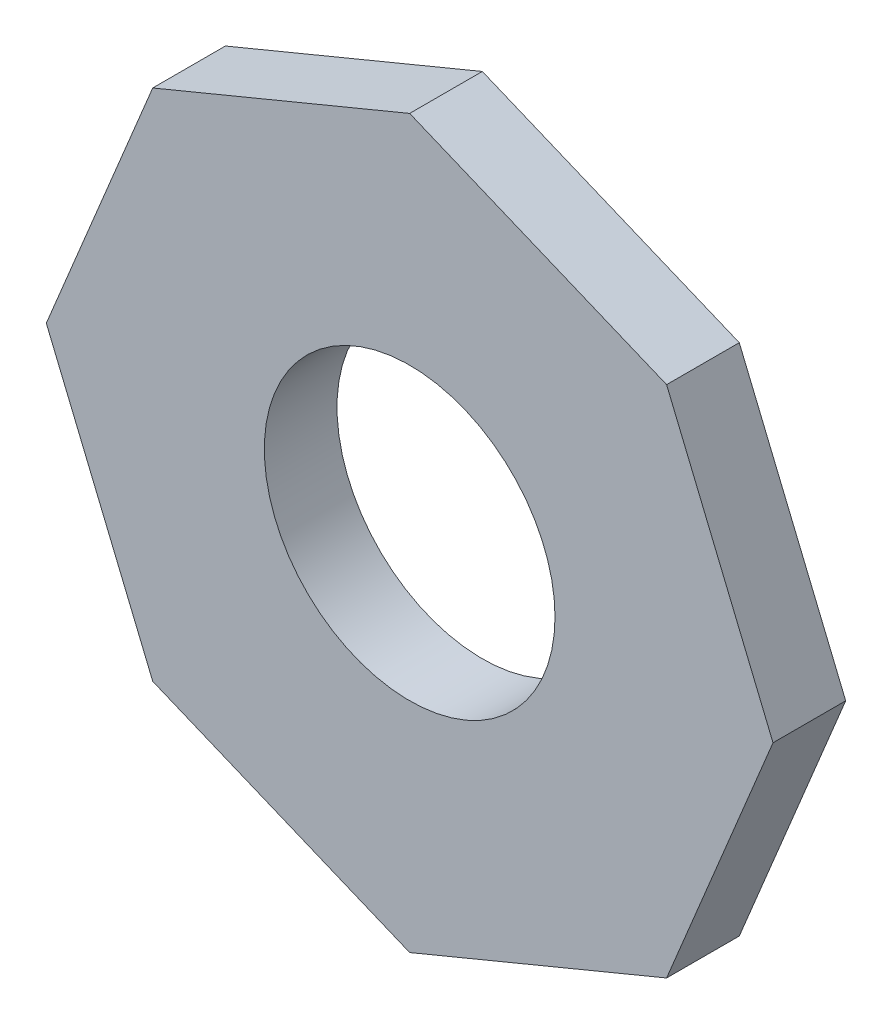
SolidWorks part; units mm, degrees
ref_plane "前视基准面" through (0, 0, 0) normal (0, 0, 1) x (1, 0, 0)
ref_plane "上视基准面" through (0, 0, 0) normal (0, 1, 0) x (1, 0, 0)
ref_plane "右视基准面" through (0, 0, 0) normal (1, 0, 0) x (0, 0, -1)
other "Configuration Table"
sketch "草图1" plane through (0, 0, 0) normal (0, 0, 1) x (1, 0, 0)
  line L1 (500, 0) -> (353.5534, 353.5534)
  line L2 (353.5534, 353.5534) -> (0, 500)
  line L3 (0, 500) -> (-353.5534, 353.5534)
  line L4 (-353.5534, 353.5534) -> (-500, 0)
  line L5 (-500, 0) -> (-353.5534, -353.5534)
  line L6 (-353.5534, -353.5534) -> (0, -500)
  line L7 (0, -500) -> (353.5534, -353.5534)
  line L8 (353.5534, -353.5534) -> (500, 0)
  circle A0 centre (0, 0) radius 461.9398 construction
extrude "凸台-拉伸1" add sketch "草图1" along normal blind 100
sketch "草图2" plane through (0, 0, 0) normal (0, 0, 1) x (1, 0, 0)
  circle A0 centre (0, 0) radius 200
extrude "切除-拉伸2" cut sketch "草图2" along normal through all
